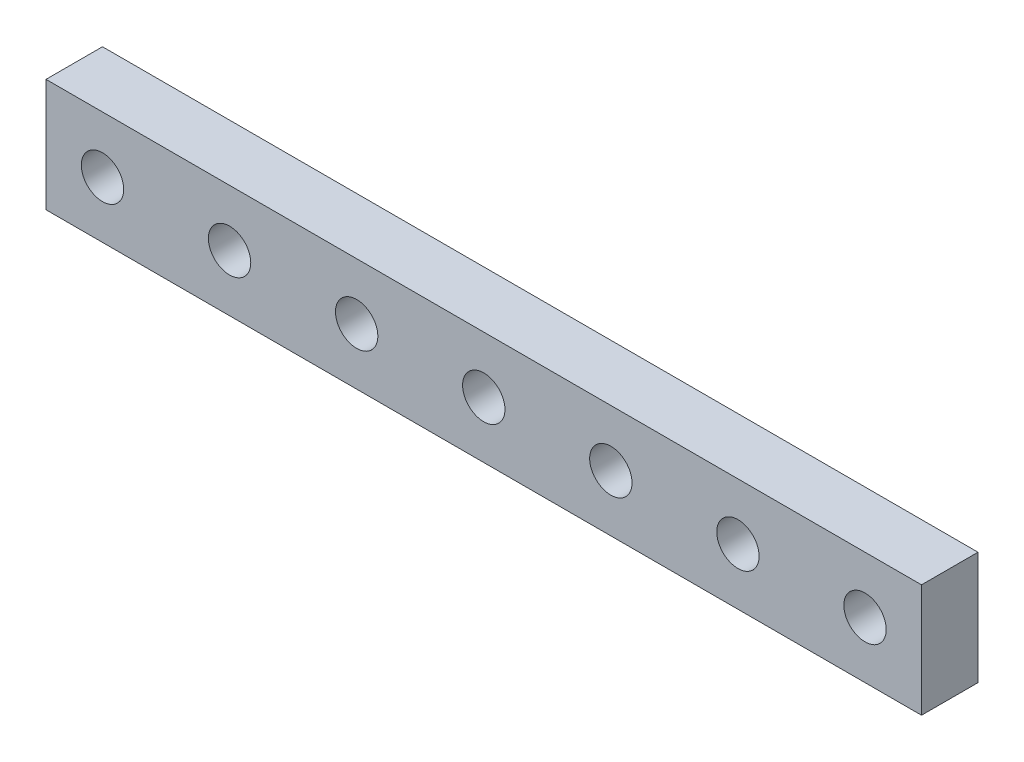
SolidWorks part; units mm, degrees
ref_plane "前视基准面" through (0, 0, 0) normal (0, 0, 1) x (1, 0, 0)
ref_plane "上视基准面" through (0, 0, 0) normal (0, 1, 0) x (1, 0, 0)
ref_plane "右视基准面" through (0, 0, 0) normal (1, 0, 0) x (0, 0, -1)
sketch "草图1" plane through (0, 0, 0) normal (0, 0, 1) x (1, 0, 0)
  line L0 (2551.3418, 1596.0677) -> (2613.3418, 1596.0677)
  line L1 (2613.3418, 1596.0677) -> (2613.3418, 1588.0677)
  line L2 (2613.3418, 1588.0677) -> (2551.3418, 1588.0677)
  line L3 (2551.3418, 1588.0677) -> (2551.3418, 1596.0677)
  circle A0 centre (2555.3418, 1592.0677) radius 1.5
  circle A1 centre (2564.3418, 1592.0677) radius 1.5
  circle A2 centre (2573.3418, 1592.0677) radius 1.5
  circle A3 centre (2582.3418, 1592.0677) radius 1.5
  circle A4 centre (2591.3418, 1592.0677) radius 1.5
  circle A5 centre (2600.3418, 1592.0677) radius 1.5
  circle A6 centre (2609.3418, 1592.0677) radius 1.5
extrude "凸台-拉伸1" add sketch "草图1" along normal blind 4
